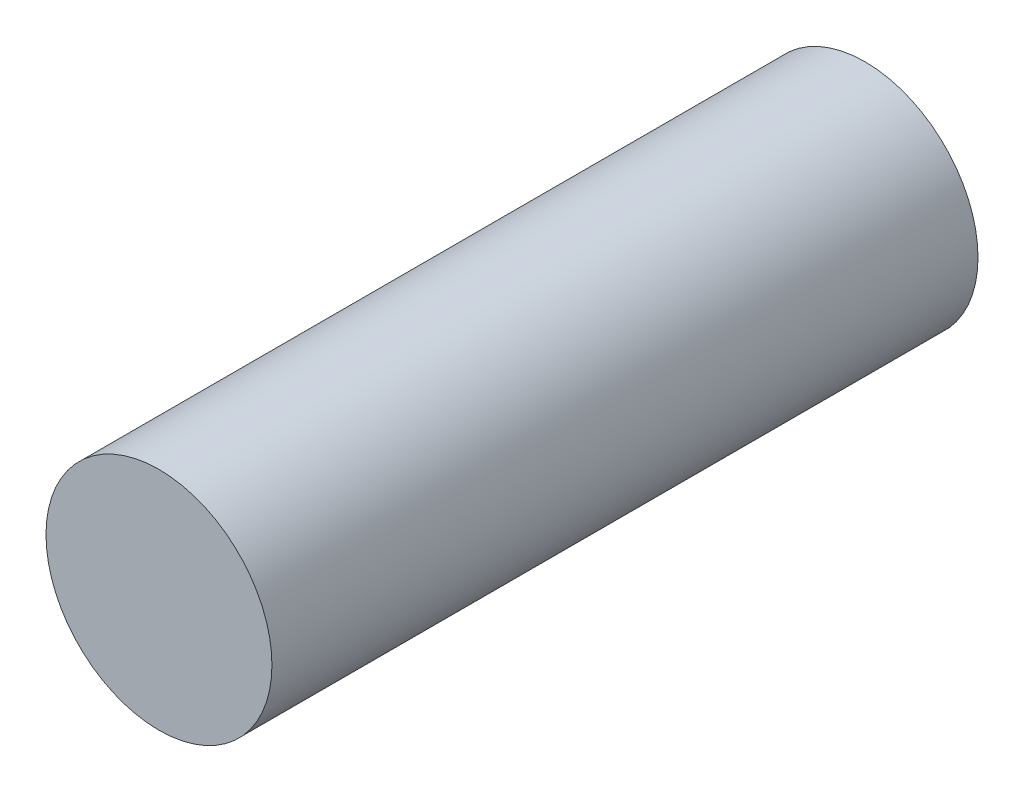
SolidWorks part; units mm, degrees
ref_plane "前视基准面" through (0, 0, 0) normal (0, 0, 1) x (1, 0, 0)
ref_plane "上视基准面" through (0, 0, 0) normal (0, 1, 0) x (1, 0, 0)
ref_plane "右视基准面" through (0, 0, 0) normal (1, 0, 0) x (0, 0, -1)
sketch "草图1" plane through (0, 0, 0) normal (0, 0, 1) x (1, 0, 0)
  circle A0 centre (0, 0) radius 4
  dimension "D1" = 8
extrude "凸台-拉伸1" add sketch "草图1" along normal blind 25
